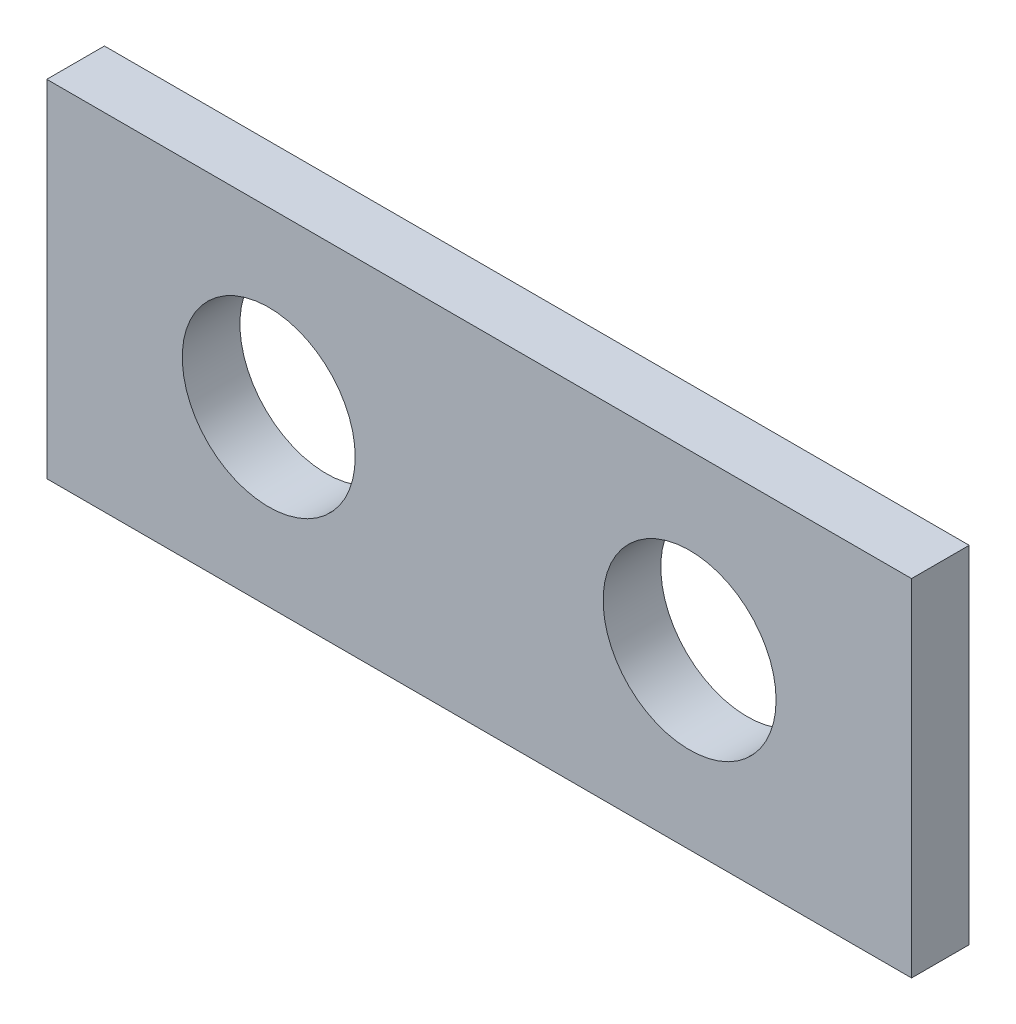
SolidWorks part; units mm, degrees
ref_plane "Front Plane" through (0, 0, 0) normal (0, 0, 1) x (1, 0, 0)
ref_plane "Top Plane" through (0, 0, 0) normal (0, 1, 0) x (1, 0, 0)
ref_plane "Right Plane" through (0, 0, 0) normal (1, 0, 0) x (0, 0, -1)
sketch "Sketch1" plane through (0, 0, 0) normal (0, 0, 1) x (1, 0, 0)
  line L0 (-15, 3) -> (0, 3) construction
  line L1 (-7.5, 6) -> (-7.5, 0) construction
  line L2 (-15, 0) -> (-15, 6)
  line L3 (-15, 6) -> (0, 6)
  line L4 (0, 6) -> (0, 0)
  line L5 (0, 0) -> (-15, 0)
  line L6 (-3.85, 3) -> (-11.15, 3) construction
  circle A0 centre (-3.85, 3) radius 1.5 construction
  circle A1 centre (-11.15, 3) radius 1.5
  circle A2 centre (-3.85, 3) radius 1.5
  circle A3 centre (-3.85, 3) radius 1.5
  point P9 (-3.85, 3)
  point P10 (-11.15, 3)
  point P14 (-18.7009, 3)
  point P15 (-7.5, 3)
  point P16 (-7.5, 3)
  dimension "D1" = 6
  dimension "D2" = 3
  dimension "D3" = 7.3
  dimension "D4" = 15
extrude "Boss-Extrude1" add sketch "Sketch1" along normal blind 1 contours L5 L4 L3 L2 A2 A1
